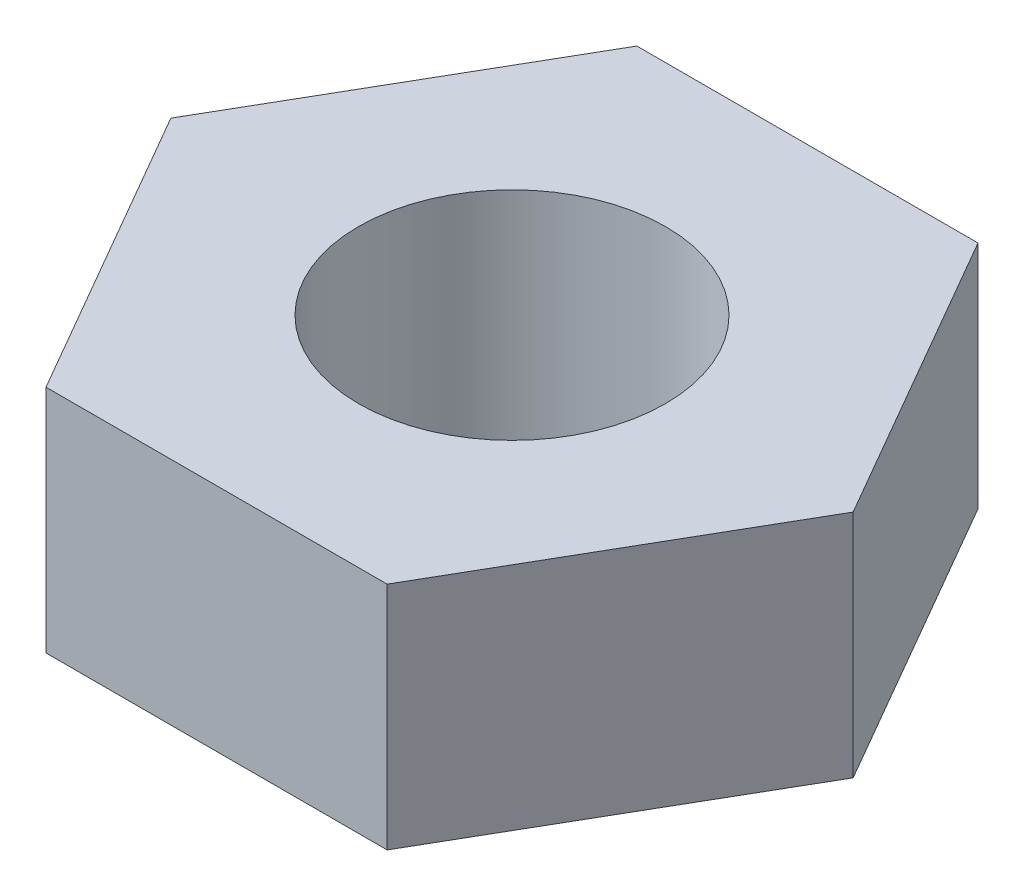
SolidWorks part; units mm, degrees
ref_plane "Front Plane" through (0, 0, 0) normal (0, 0, 1) x (1, 0, 0)
ref_plane "Top Plane" through (0, 0, 0) normal (0, 1, 0) x (1, 0, 0)
ref_plane "Right Plane" through (0, 0, 0) normal (1, 0, 0) x (0, 0, -1)
other "Configuration Table"
sketch "Sketch1" plane through (0, 0, 0) normal (0, 1, 0) x (1, 0, 0)
  line L1 (1.1114, 1.925) -> (-1.1114, 1.925)
  line L2 (-1.1114, 1.925) -> (-2.2228, 0)
  line L3 (-2.2228, 0) -> (-1.1114, -1.925)
  line L4 (-1.1114, -1.925) -> (1.1114, -1.925)
  line L5 (1.1114, -1.925) -> (2.2228, 0)
  line L6 (2.2228, 0) -> (1.1114, 1.925)
  circle A0 centre (0, 0) radius 1.925 construction
  circle A1 centre (0, 0) radius 1
  dimension "D1" = 3.85
  dimension "D2" = 2
extrude "Boss-Extrude1" add sketch "Sketch1" along normal blind 1.5
